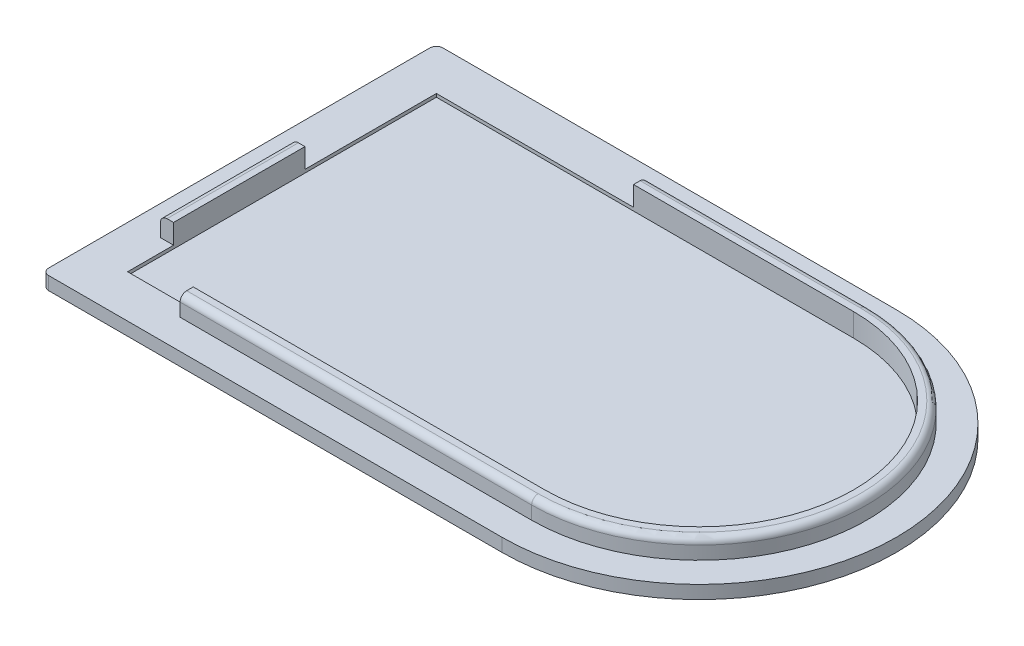
SolidWorks part; units mm, degrees
ref_plane "Front Plane" through (0, 0, 0) normal (0, 0, 1) x (1, 0, 0)
ref_plane "Top Plane" through (0, 0, 0) normal (0, 1, 0) x (1, 0, 0)
ref_plane "Right Plane" through (0, 0, 0) normal (1, 0, 0) x (0, 0, -1)
sketch "Sketch1" plane through (0, 0, 0) normal (0, 1, 0) x (1, 0, 0)
  line L1 (0, 25.5) -> (-65.5, 25.5)
  line L3 (0, -25.5) -> (-65.5, -25.5)
  line L4 (-65.5, 25.5) -> (-65.5, -25.5)
  circle A0 centre (0, 0) radius 25.5
  dimension "D1" = 65.5
  dimension "D2" = 51
  dimension "D3" = 51
extrude "Boss-Extrude1" add sketch "Sketch1" along normal blind 3 contours A0 L1 L4 L3 | A0 L1
sketch "Sketch2" plane through (0, 0, 0) normal (0, -1, 0) x (1, 0, 0)
  line L0 (-70, 30) -> (0, 30)
  line L1 (-65.5, 25.5) -> (0, 25.5)
  line L2 (-65.5, 25.5) -> (-65.5, -25.5)
  line L3 (-65.5, -25.5) -> (0, -25.5)
  line L5 (-70, -30) -> (0, -30)
  line L6 (-70, 30) -> (-70, -30)
  arc A0 (0, -25.5) -> (0, 25.5) centre (0, 0) ccw
  arc A1 (0, -30) -> (0, 30) centre (0, 0) ccw
  line M10 (0, 25.5) -> (-65.5, 25.5)
  line M11 (-65.5, 25.5) -> (-65.5, -25.5)
  line M12 (-65.5, -25.5) -> (0, -25.5)
  arc M13 (0, -25.5) -> (0, 25.5) centre (0, 0) ccw
  dimension "D1" = 4.5
extrude "Boss-Extrude2" add sketch "Sketch2" along normal blind 2 contours M13 M10 M11 M12 | L5 A1 L0 L6 M10 M13 M12 M11
sketch "Sketch4" plane through (0, 3, 0) normal (0, 1, 0) x (1, 0, 0)
  line L0 (-63.5, 23.5) -> (-63.5, -23.5)
  line L1 (-65.5, 25.5) -> (0, 25.5)
  line L2 (-65.5, 25.5) -> (-65.5, -25.5)
  line L3 (-65.5, -25.5) -> (0, -25.5)
  line L4 (-63.5, -23.5) -> (0, -23.5)
  line L5 (-63.5, 23.5) -> (0, 23.5)
  arc A0 (0, -25.5) -> (0, 25.5) centre (0, 0) ccw
  arc A1 (0, -23.5) -> (0, 23.5) centre (0, 0) ccw
  dimension "D1" = 2
extrude "Cut-Extrude1" cut sketch "Sketch4" against normal blind 3.5 contours L4 A1 L5 L0
fillet "Fillet1" radius 1 2 edges at (-70, -1, -30) (-70, -1, 30)
sketch "Sketch5" plane through (0, 3, 0) normal (0, 1, 0) x (1, 0, 0)
  line L1 (-65.5, 25.5) -> (-53.5, 25.5)
  line L2 (-65.5, 25.5) -> (-65.5, 16.5)
  line L5 (-65.5, -25.5) -> (-53.5, -25.5)
  line L6 (-65.5, -25.5) -> (-65.5, -16.5)
  line L9 (-65.5, -25.5) -> (-53.5, -25.5)
  line L10 (-65.5, -25.5) -> (-65.5, -16.5)
  line L11 (-65.5, -16.5) -> (-53.5, -16.5)
  line L12 (-53.5, -25.5) -> (-53.5, -16.5)
  line L13 (-65.5, 25.5) -> (-33.5, 25.5)
  line L14 (-65.5, 25.5) -> (-65.5, 3.5)
  line L15 (-65.5, 3.5) -> (-33.5, 3.5)
  line L16 (-33.5, 25.5) -> (-33.5, 3.5)
  line M1 (0, -23.5) -> (-63.5, -23.5)
  line M2 (-63.5, -23.5) -> (-63.5, 23.5)
  line M3 (-63.5, 23.5) -> (0, 23.5)
  line M5 (-65.5, -25.5) -> (0, -25.5)
  line M8 (-65.5, 25.5) -> (-65.5, -25.5)
  dimension "D1" = 12
  dimension "D2" = 9
  dimension "D5" = 12
  dimension "D6" = 9
  dimension "D7" = 22
  dimension "D8" = 32
extrude "Cut-Extrude4" cut sketch "Sketch5" against normal up to surface (3 mm away) contours L12 L11 M1 M2 | L12 L11 M5 M1 M2 M8 | L16 L15 M3 M2
fillet "Fillet8" radius 1 1 edges at (-65.5, 3, 6.5)
fillet "Fillet9" radius 1 3 edges at (25.5, 3, 0) (-16.75, 3, -25.5) (-26.75, 3, 25.5)
